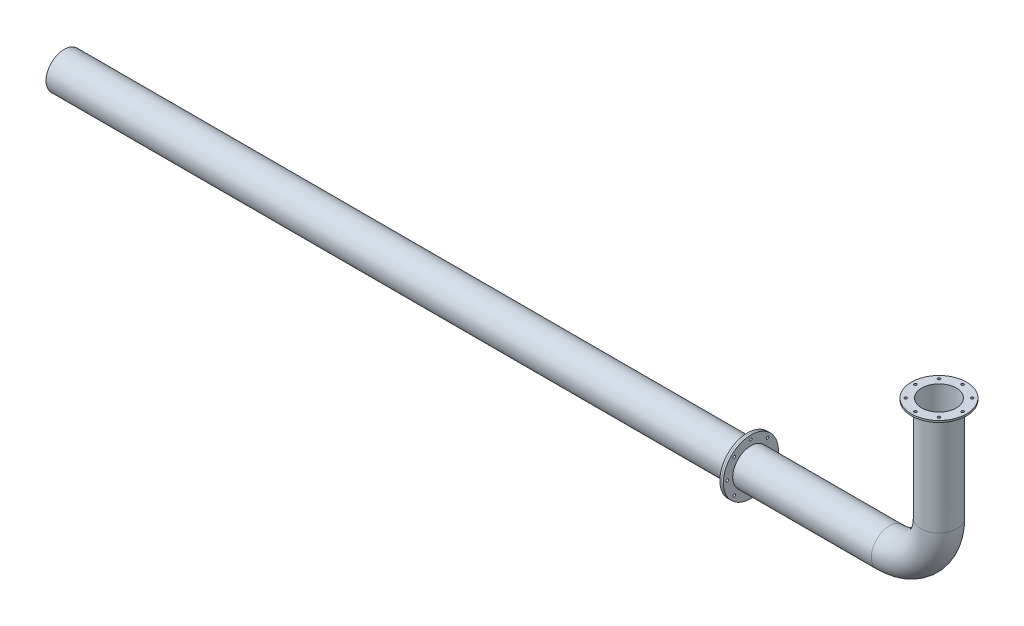
SolidWorks part; units mm, degrees
ref_plane "Front Plane" through (0, 0, 0) normal (0, 0, 1) x (1, 0, 0)
ref_plane "Top Plane" through (0, 0, 0) normal (0, 1, 0) x (1, 0, 0)
ref_plane "Right Plane" through (0, 0, 0) normal (1, 0, 0) x (0, 0, -1)
sketch "Sketch1" plane through (0, 0, 0) normal (0, 1, 0) x (1, 0, 0)
  line L0 (0, 0) -> (0, 127.5) construction
  circle A0 centre (0, 0) radius 127.5
  circle A1 centre (0, 109) radius 6
  circle A2 centre (0, 0) radius 80
  circle A3 centre (77.0746, 77.0746) radius 6
  circle A4 centre (109, 0) radius 6
  circle A5 centre (77.0746, -77.0746) radius 6
  circle A6 centre (0, -109) radius 6
  circle A7 centre (-77.0746, -77.0746) radius 6
  circle A8 centre (-109, 0) radius 6
  circle A9 centre (-77.0746, 77.0746) radius 6
  point P8 (0, 0)
  point P24 (0, 0)
  dimension "D1" = 255
  dimension "D2" = 12
  dimension "D4" = 160
  dimension "D3" = 109
  dimension "D5" = 8
extrude "Boss-Extrude1" add sketch "Sketch1" along normal blind 8
sketch "Sketch2" plane through (0, 0, 0) normal (0, -1, 0) x (1, 0, 0)
  circle A0 centre (0, 0) radius 80
  circle A1 centre (0, 0) radius 84
  dimension "D1" = 168
extrude "Boss-Extrude2" add sketch "Sketch2" along normal blind 473.1
sketch "Sketch3" plane through (0, -473.1, 0) normal (0, -1, 0) x (1, 0, 0)
  circle A0 centre (0, 0) radius 80 construction
  circle A1 centre (0, 0) radius 84
  circle A2 centre (0, 0) radius 84
  circle A3 centre (0, 0) radius 80
  dimension "D1" = 0
sketch "Sketch5" plane through (0, 0, 0) normal (0, 0, 1) x (1, 0, 0)
  line L0 (0, -473.1) -> (-228.6, -473.1) construction
  line L1 (-228.6, -473.1) -> (-228.6, -701.7) construction
  arc A0 (0, -473.1) -> (-228.6, -701.7) centre (-228.6, -473.1) cw
  dimension "D1" = 228.6
sweep "Sweep1" add profiles "Sketch3" path "Sketch5"
sketch "Sketch6" plane through (-228.6, 0, 0) normal (-1, 0, 0) x (0, 0, 1)
  circle A0 centre (0, -701.7) radius 80 construction
  circle A1 centre (0, -701.7) radius 84
  circle A2 centre (0, -701.7) radius 84
  circle A3 centre (0, -701.7) radius 80
  dimension "D1" = 0
extrude "Boss-Extrude3" add sketch "Sketch6" along normal blind 640.58
sketch "Sketch7" plane through (-869.18, 0, 0) normal (-1, 0, 0) x (0, 0, 1)
  line L10 (0, -701.7) -> (0, -574.2) construction
  circle A0 centre (0, -701.7) radius 80
  circle A1 centre (0, -701.7) radius 127.5
  circle A3 centre (0, -592.7) radius 6
  circle A4 centre (0, -701.7) radius 35 construction
  circle A5 centre (77.0746, -624.6254) radius 6
  circle A6 centre (109, -701.7) radius 6
  circle A7 centre (77.0746, -778.7746) radius 6
  circle A8 centre (0, -810.7) radius 6
  circle A9 centre (-77.0746, -778.7746) radius 6
  circle A10 centre (-109, -701.7) radius 6
  circle A11 centre (-77.0746, -624.6254) radius 6
  point P9 (0, -701.7)
  point P26 (0, -701.7)
  dimension "D1" = 255
  dimension "D2" = 12
  dimension "D4" = 70
  dimension "D3" = 109
  dimension "D5" = 8
extrude "Boss-Extrude4" add sketch "Sketch7" along normal blind 8
sketch "Sketch8" plane through (-877.18, 0, 0) normal (-1, 0, 0) x (0, 0, 1)
  circle A0 centre (-109, -701.7) radius 6 construction
  circle A1 centre (0, -701.7) radius 127.5
  circle A2 centre (0, -701.7) radius 127.5
  circle A3 centre (-77.0746, -624.6254) radius 6 construction
  circle A4 centre (0, -592.7) radius 6 construction
  circle A5 centre (77.0746, -624.6254) radius 6 construction
  circle A6 centre (109, -701.7) radius 6 construction
  circle A7 centre (77.0746, -778.7746) radius 6 construction
  circle A8 centre (0, -810.7) radius 6 construction
  circle A9 centre (-77.0746, -778.7746) radius 6 construction
  circle A10 centre (0, -701.7) radius 80 construction
  circle A11 centre (-109, -701.7) radius 6
  circle A12 centre (-77.0746, -624.6254) radius 6
  circle A13 centre (0, -592.7) radius 6
  circle A14 centre (77.0746, -624.6254) radius 6
  circle A15 centre (109, -701.7) radius 6
  circle A16 centre (77.0746, -778.7746) radius 6
  circle A17 centre (0, -810.7) radius 6
  circle A18 centre (-77.0746, -778.7746) radius 6
  circle A19 centre (0, -701.7) radius 80
  dimension "D1" = 0
extrude "Boss-Extrude5" add sketch "Sketch8" along normal blind 8 separate body
sketch "Sketch9" plane through (-885.18, 0, 0) normal (-1, 0, 0) x (0, 0, 1)
  circle A0 centre (0, -701.7) radius 80
  circle A1 centre (0, -701.7) radius 84
  dimension "D1" = 168
extrude "Boss-Extrude6" add sketch "Sketch9" along normal blind 3157
